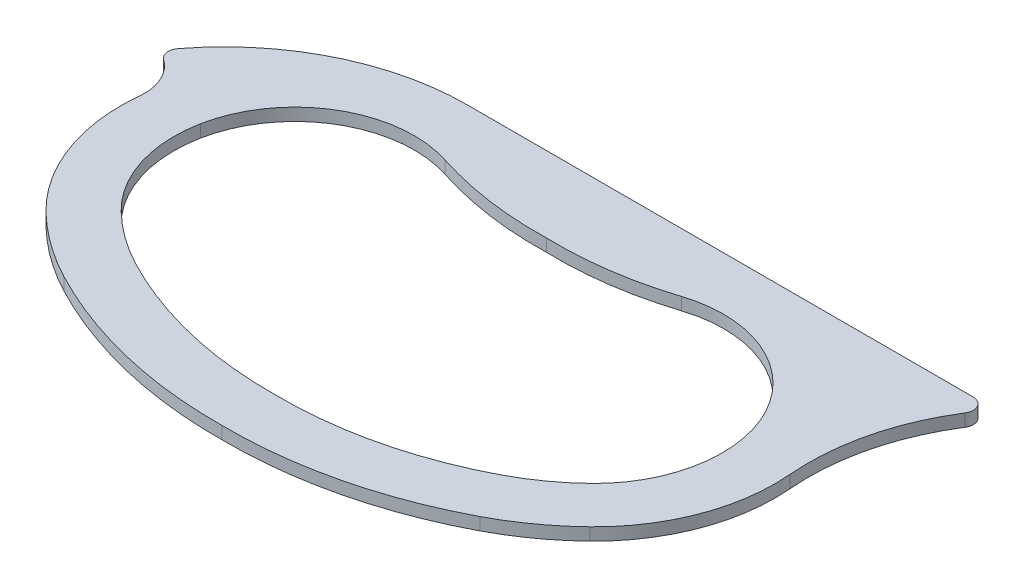
SolidWorks part; units mm, degrees
ref_plane "Front Plane" through (0, 0, 0) normal (0, 0, 1) x (1, 0, 0)
ref_plane "Top Plane" through (0, 0, 0) normal (0, 1, 0) x (1, 0, 0)
ref_plane "Right Plane" through (0, 0, 0) normal (1, 0, 0) x (0, 0, -1)
sketch "Sketch1" plane through (0, 0, 0) normal (0, 1, 0) x (1, 0, 0)
  line L6 (5.5144, 3.92) -> (5.5144, -71.4808) construction
  line L7 (5.5144, 3.92) -> (32.4758, 7.7373) construction
  line L8 (32.4758, 7.7373) -> (75.9016, -17.9694) construction
  line L9 (75.9016, -17.9694) -> (65.6428, -50.4744) construction
  line L10 (65.6428, -50.4744) -> (51.9947, -60.3309) construction
  line L11 (51.9947, -60.3309) -> (5.5144, -71.4808) construction
  line L12 (98.057, 19.3468) -> (-31.7447, 19.3468) construction
  line L14 (95.9097, 17.3468) -> (-31.7447, 17.3468) construction
  line L15 (-31.7447, 17.3468) -> (90.1126, 17.3468) construction
  line L16 (-31.7447, 17.1468) -> (90.1126, 17.1468)
  arc A10 (5.5144, 3.92) -> (32.4758, 7.7373) centre (7.8394, 84.6206) ccw construction
  arc A11 (32.4758, 7.7373) -> (75.9016, -17.9694) centre (42.7736, -24.3994) cw construction
  arc A12 (75.9016, -17.9694) -> (65.6428, -50.4744) centre (40.8392, -24.7748) cw construction
  arc A13 (65.6428, -50.4744) -> (51.9947, -60.3309) centre (24.395, -7.7366) cw construction
  arc A14 (51.9947, -60.3309) -> (5.5144, -71.4808) centre (6.7215, 25.9423) cw construction
  arc A15 (-40.9658, -60.3309) -> (5.5144, -71.4808) centre (4.3074, 25.9423) ccw construction
  arc A16 (-54.6139, -50.4744) -> (-40.9658, -60.3309) centre (-13.3661, -7.7366) ccw construction
  arc A17 (-64.8727, -17.9694) -> (-54.6139, -50.4744) centre (-29.8104, -24.7748) ccw construction
  arc A18 (-21.4469, 7.7373) -> (-64.8727, -17.9694) centre (-31.7447, -24.3994) ccw construction
  arc A19 (5.5144, 3.92) -> (-21.4469, 7.7373) centre (3.1894, 84.6206) cw construction
  arc A20 (98.057, 19.3468) -> (103.2568, 24.5028) centre (98.057, 24.5468) ccw construction
  arc A21 (-31.7447, 19.3468) -> (-82.3659, -7.8265) centre (-31.7447, -41.3909) ccw construction
  arc A22 (-82.3659, -7.8265) -> (-85.9228, -10.0945) centre (-86.6998, -4.9529) cw construction
  arc A23 (98.057, 19.3468) -> (101.7184, 20.8543) centre (98.057, 24.5468) ccw construction
  arc A24 (5.5144, -1.082) -> (34.0016, 2.9757) centre (7.8394, 84.6206) ccw
  arc A25 (101.7184, 20.8543) -> (86.389, -20.8715) centre (138.6513, -16.393) ccw construction
  arc A26 (-85.9228, -10.0945) -> (-75.2979, -20.203) centre (-84.5355, -19.2745) cw construction
  arc A27 (-61.5585, -57.6698) -> (-45.6125, -69.1857) centre (-13.3661, -7.7366) ccw construction
  arc A28 (-45.6125, -69.1857) -> (5.5144, -81.4815) centre (4.3074, 25.9423) ccw construction
  arc A29 (56.6414, -69.1857) -> (5.5144, -81.4815) centre (6.7215, 25.9423) cw construction
  arc A30 (72.5873, -57.6698) -> (56.6414, -69.1857) centre (24.395, -7.7366) cw construction
  arc A31 (85.7184, -16.0641) -> (72.5873, -57.6698) centre (40.8392, -24.7748) cw construction
  arc A32 (29.4243, 17.2603) -> (85.7184, -16.0641) centre (42.7736, -24.3994) cw construction
  arc A33 (5.5144, 13.9247) -> (29.4243, 17.2603) centre (7.8394, 84.6206) ccw construction
  arc A34 (5.5144, 13.9247) -> (-18.3954, 17.2603) centre (3.1894, 84.6206) cw construction
  arc A35 (-18.3954, 17.2603) -> (-74.6895, -16.0641) centre (-31.7447, -24.3994) ccw construction
  arc A36 (-74.6895, -16.0641) -> (-61.5585, -57.6698) centre (-29.8104, -24.7748) ccw construction
  arc A37 (-61.5585, -57.6698) -> (-75.2979, -20.203) centre (-29.8104, -24.7748) cw construction
  arc A38 (86.389, -20.8715) -> (72.5873, -57.6698) centre (40.8392, -24.7748) cw construction
  arc A42 (-60.1696, -56.2307) -> (-73.3079, -20.403) centre (-29.8104, -24.7748) cw construction
  arc A43 (-60.1696, -56.2307) -> (-44.6831, -67.4147) centre (-13.3661, -7.7366) ccw construction
  arc A44 (-44.6831, -67.4147) -> (5.5144, -79.4814) centre (4.3074, 25.9423) ccw construction
  arc A45 (55.712, -67.4147) -> (5.5144, -79.4814) centre (6.7215, 25.9423) cw construction
  arc A46 (71.1984, -56.2307) -> (55.712, -67.4147) centre (24.395, -7.7366) cw construction
  arc A47 (84.3963, -21.0423) -> (71.1984, -56.2307) centre (40.8392, -24.7748) cw construction
  arc A48 (92.6471, 12.7417) -> (84.3963, -21.0423) centre (138.6513, -16.393) ccw construction
  arc A50 (95.9097, 17.3468) -> (95.9097, 17.3468) centre (95.9097, 17.3468) cw construction
  arc A51 (-31.7447, 17.3468) -> (-80.5551, -8.7157) centre (-31.7447, -41.3909) ccw construction
  arc A53 (-80.5551, -8.7157) -> (-80.5551, -8.7157) centre (-80.5551, -8.7157) ccw construction
  arc A54 (-80.5551, -8.7157) -> (-73.3079, -20.403) centre (-84.5355, -19.2745) cw construction
  arc A55 (-31.7447, 17.3468) -> (-78.544, -5.8951) centre (-31.7447, -41.3909) ccw construction
  arc A56 (-77.9141, -10.1372) -> (-73.3079, -20.403) centre (-84.5355, -19.2745) cw construction
  arc A57 (-78.544, -5.8951) -> (-77.9141, -10.1372) centre (-76.1537, -7.708) ccw construction
  arc A58 (95.9097, 17.3468) -> (84.3963, -21.0423) centre (138.6513, -16.393) ccw construction
  arc A59 (92.6471, 12.7417) -> (90.1126, 17.3468) centre (90.1126, 14.3468) ccw construction
  arc A60 (92.4781, 12.8487) -> (90.1126, 17.1468) centre (90.1126, 14.3468) ccw
  arc A61 (92.4781, 12.8487) -> (84.197, -21.0594) centre (138.6513, -16.393) ccw
  arc A62 (84.197, -21.0594) -> (71.0595, -56.0868) centre (40.8392, -24.7748) cw
  arc A63 (71.0595, -56.0868) -> (55.6191, -67.2376) centre (24.395, -7.7366) cw
  arc A64 (55.6191, -67.2376) -> (5.5144, -79.2814) centre (6.7215, 25.9423) cw
  arc A65 (-44.5902, -67.2376) -> (5.5144, -79.2814) centre (4.3074, 25.9423) ccw
  arc A66 (-60.0307, -56.0868) -> (-44.5902, -67.2376) centre (-13.3661, -7.7366) ccw
  arc A67 (-60.0307, -56.0868) -> (-73.1089, -20.423) centre (-29.8104, -24.7748) cw
  arc A68 (-77.7967, -9.9753) -> (-73.1089, -20.423) centre (-84.5355, -19.2745) cw
  arc A69 (-78.3846, -6.016) -> (-77.7967, -9.9753) centre (-76.1537, -7.708) ccw
  arc A70 (-31.7447, 17.1468) -> (-78.3846, -6.016) centre (-31.7447, -41.3909) ccw
  arc A71 (34.0016, 2.9757) -> (70.9932, -18.9221) centre (42.7736, -24.3994) cw
  arc A72 (70.9932, -18.9221) -> (62.1705, -46.8767) centre (40.8392, -24.7748) cw
  arc A73 (62.1705, -46.8767) -> (49.6713, -55.9035) centre (24.395, -7.7366) cw
  arc A74 (49.6713, -55.9035) -> (5.5144, -66.4804) centre (6.7215, 25.9423) cw
  arc A75 (-38.6424, -55.9035) -> (5.5144, -66.4804) centre (4.3074, 25.9423) ccw
  arc A76 (-51.1417, -46.8767) -> (-38.6424, -55.9035) centre (-13.3661, -7.7366) ccw
  arc A77 (-59.9643, -18.9221) -> (-51.1417, -46.8767) centre (-29.8104, -24.7748) ccw
  arc A78 (-22.9727, 2.9757) -> (-59.9643, -18.9221) centre (-31.7447, -24.3994) ccw
  arc A79 (5.5144, -1.082) -> (-22.9727, 2.9757) centre (3.1894, 84.6206) cw
  dimension "D2" = 27.2303
  dimension "D20" = 9.2842
  dimension "D7" = 80.7341
  dimension "D13" = 3
  dimension "D15" = 5
  dimension "D17" = 52.4539
  dimension "D19" = 5.2
  dimension "D1" = 75.4008
  dimension "D3" = 50.4642
  dimension "D4" = 34.0854
  dimension "D5" = 47.7989
  dimension "D6" = 16.8352
  dimension "D8" = 103.108
  dimension "D9" = 98.059
  dimension "D10" = 76.51
  dimension "D11" = 10
  dimension "D12" = 2
  dimension "D14" = 0.2
extrude "Boss-Extrude1" add sketch "Sketch1" along normal blind 3
